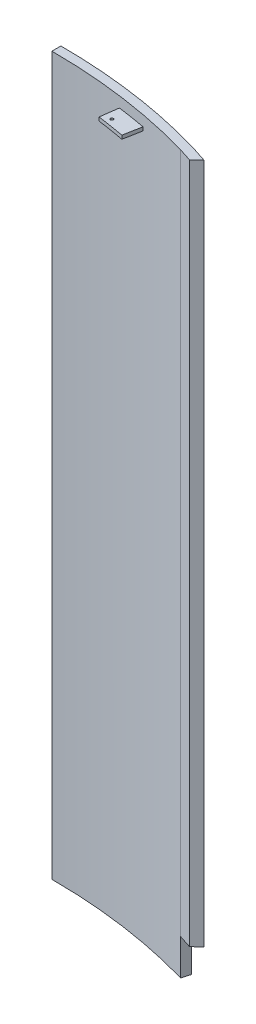
SolidWorks part; units mm, degrees
ref_plane "前视基准面" through (0, 0, 0) normal (0, 0, 1) x (1, 0, 0)
ref_plane "上视基准面" through (0, 0, 0) normal (0, 1, 0) x (1, 0, 0)
ref_plane "右视基准面" through (0, 0, 0) normal (1, 0, 0) x (0, 0, -1)
sketch "草图1" plane through (0, 0, 0) normal (0, 1, 0) x (1, 0, 0)
  line L0 (0, 0) -> (0, 1540) construction
  line L1 (424.4815, 1480.343) -> (0, 0) construction
  line L2 (0, 1540) -> (0, 1515)
  line L3 (424.4815, 1480.343) -> (417.5906, 1456.3115)
  arc A0 (0, 1540) -> (424.4815, 1480.343) centre (0, 0) cw
  arc A1 (0, 1515) -> (417.5906, 1456.3115) centre (0, 0) cw
  dimension "D3" = 1515
  dimension "D1" = 1540
  dimension "D2" = 16
extrude "凸台-拉伸1" add sketch "草图1" along normal blind 2000
sketch "草图2" plane through (0, 2000, 0) normal (0, 1, 0) x (1, 0, 0)
  line L0 (0, 0) -> (-494.4272, -1521.6904) construction
  line L1 (0, 0) -> (-494.4272, -1521.6904)
  line L2 (424.4815, 1480.343) -> (475.5963, 1463.7348)
  line L3 (417.5906, 1456.3115) -> (467.8756, 1439.9729)
  line L4 (214.3266, 1525.0128) -> (210.8472, 1500.2561) construction
  line L5 (475.5963, 1463.7348) -> (454.1566, 1444.4305)
  line L6 (417.5906, 1456.3115) -> (424.4815, 1480.343)
  line L7 (0, 1515) -> (0, 1540)
  line L8 (-53.7125, 1538.1243) -> (-38.4244, 1513.6582)
  line L9 (0, 1515) -> (-52.8405, 1513.1548)
  line L10 (0, 1540) -> (-53.7125, 1538.1243)
  arc A0 (424.4815, 1480.343) -> (0, 1540) centre (0, 0) ccw construction
  arc A1 (417.5906, 1456.3115) -> (0, 1515) centre (0, 0) ccw construction
  line M8 (417.5906, 1456.3115) -> (424.4815, 1480.343)
  dimension "D1" = 60
extrude "凸台-拉伸2" add sketch "草图2" against normal up to surface (1900 mm away) contours L5 L2 L3 M8
ref_plane "基准面1" through (0, 1970.4, 0) normal (0, 1, 0) x (1, 0, 0)
sketch "草图3" plane through (0, 1970.4, 0) normal (0, 1, 0) x (1, 0, 0)
  line L0 (424.4815, 1480.343) -> (475.5963, 1463.7348) construction
  line L1 (424.4815, 1480.343) -> (475.5963, 1463.7348) construction
  line L2 (0, 0) -> (475.5963, 1463.7348) construction
  line L3 (0, 0) -> (-1756.0224, 570.5663) construction
  line L4 (0, 0) -> (-619.2, 1215.2485) construction
  line L5 (0, 0) -> (163.3361, 1216.0511) construction
  line L6 (163.3361, 1216.0511) -> (201.6788, 1501.5161) construction
  line L7 (201.6788, 1501.5161) -> (194.963, 1451.5161)
  line L8 (279.9857, 1488.9033) -> (270.6623, 1439.3233)
  arc A0 (417.5906, 1456.3115) -> (0, 1515) centre (0, 0) ccw construction
  arc A1 (417.5906, 1456.3115) -> (0, 1515) centre (0, 0) ccw construction
  arc A2 (201.6788, 1501.5161) -> (279.9857, 1488.9033) centre (0, 0) cw
  arc A3 (194.963, 1451.5161) -> (270.6623, 1439.3233) centre (0, 0) cw
  dimension "D1" = 90
  dimension "D2" = 45
  dimension "D3" = 34.65
  dimension "D4" = 50
extrude "凸台-拉伸3" add sketch "草图3" against normal blind 10
sketch "草图4" plane through (0, 1970.4, 0) normal (0, 1, 0) x (1, 0, 0)
  circle A0 centre (217.8897, 1464.1471) radius 4 construction
  circle A1 centre (217.8897, 1464.1471) radius 4
extrude "切除-拉伸1" cut sketch "草图4" against normal blind 10
